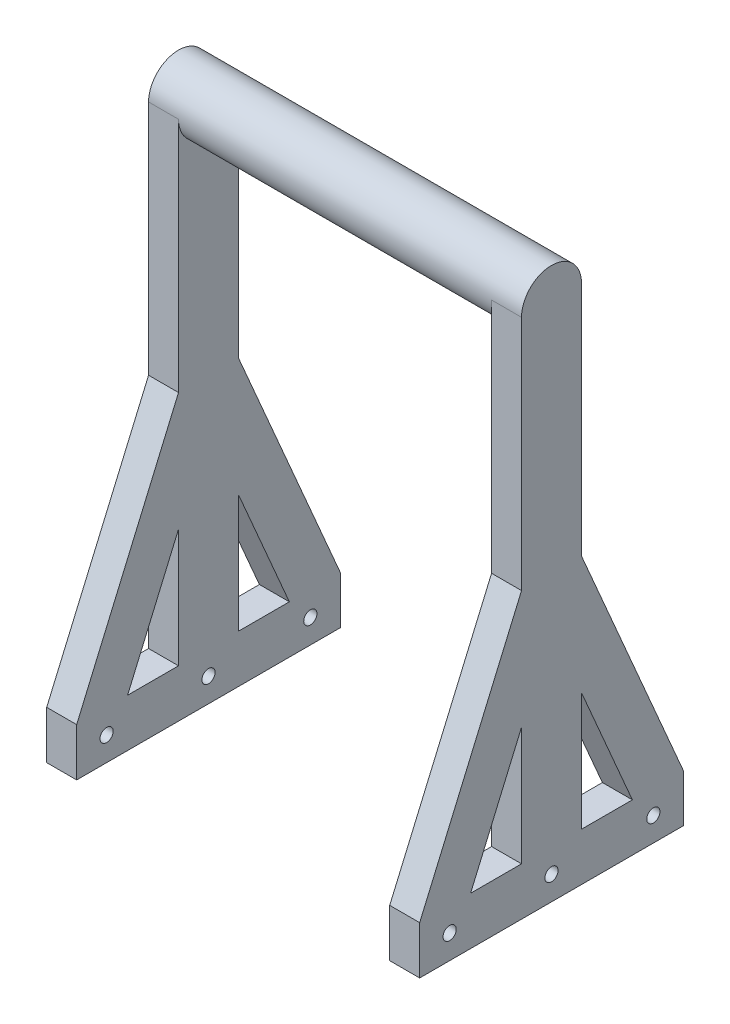
SolidWorks part; units mm, degrees
ref_plane "前视基准面" through (0, 0, 0) normal (0, 0, 1) x (1, 0, 0)
ref_plane "上视基准面" through (0, 0, 0) normal (0, 1, 0) x (1, 0, 0)
ref_plane "右视基准面" through (0, 0, 0) normal (1, 0, 0) x (0, 0, -1)
sketch "草图2" plane through (0, 0, 0) normal (0, 1, 0) x (1, 0, 0)
  line L0 (0, 27.4644) -> (0, -23.7489) construction
  line L1 (-36.2271, 0) -> (41.5528, 0) construction
  line L3 (-62.25, 44) -> (-52.25, 44)
  line L4 (-62.25, 44) -> (-62.25, -44)
  line L5 (-62.25, -44) -> (-52.25, -44)
  line L6 (-52.25, 44) -> (-52.25, -44)
  line L7 (-62.25, 44) -> (-52.25, -44) construction
  line L8 (-62.25, -44) -> (-52.25, 44) construction
  line L9 (52.25, 44) -> (62.25, 44)
  line L10 (52.25, 44) -> (52.25, -44)
  line L11 (52.25, -44) -> (62.25, -44)
  line L12 (62.25, 44) -> (62.25, -44)
  line L13 (52.25, 44) -> (62.25, -44) construction
  line L14 (52.25, -44) -> (62.25, 44) construction
  point P5 (-57.25, 0)
  point P10 (57.25, 0)
  dimension "D1" = 52.25
  dimension "D2" = 52.25
  dimension "D3" = 10
  dimension "D4" = 10
  dimension "D5" = 88
  dimension "D6" = 88
extrude "凸台-拉伸1" add sketch "草图2" along normal blind 16
sketch "草图3" plane through (0, 16, 0) normal (0, 1, 0) x (1, 0, 0)
  line L0 (0, 44.2315) -> (0, -45.1645) construction
  line L1 (-40.542, 0) -> (49.5325, 0) construction
  line L2 (-62.25, 44) -> (-62.25, -44) construction
  line L3 (-62.25, 10) -> (-52.25, 10)
  line L4 (-62.25, 10) -> (-62.25, -10)
  line L5 (-62.25, -10) -> (-52.25, -10)
  line L6 (-52.25, 10) -> (-52.25, -10)
  line L7 (-52.25, -44) -> (-52.25, 44) construction
  line L8 (62.25, -10) -> (52.25, -10)
  line L9 (52.25, 10) -> (52.25, -10)
  line L10 (62.25, 10) -> (52.25, 10)
  line L11 (62.25, 10) -> (62.25, -10)
  dimension "D1" = 10
  dimension "D2" = 10
extrude "凸台-拉伸2" add sketch "草图3" along normal blind 158
sketch "草图4" plane through (-62.25, 0, 0) normal (-1, 0, 0) x (0, 0, 1)
  line L0 (-10, 174) -> (10, 174) construction
  circle A0 centre (0, 174) radius 10
extrude "凸台-拉伸3" add sketch "草图4" against normal blind 124.5
sketch "草图5" plane through (-62.25, 0, 0) normal (-1, 0, 0) x (0, 0, 1)
  line L0 (-44, 8) -> (44, 8) construction
  line L1 (-44, 16) -> (-44, 0) construction
  line L2 (44, 16) -> (44, 0) construction
  line L3 (0, 112.2704) -> (0, 0) construction
  circle A0 centre (0, 8) radius 2.2
  circle A1 centre (-34, 8) radius 2.2
  circle A2 centre (34, 8) radius 2.2
  dimension "D1" = 4.4
  dimension "D2" = 4.4
  dimension "D3" = 4.4
  dimension "D4" = 34
  dimension "D5" = 34
extrude "切除-拉伸1" cut sketch "草图5" against normal blind 126
sketch "草图6" plane through (-62.25, 0, 0) normal (-1, 0, 0) x (0, 0, 1)
  line L0 (-44, 16) -> (-10, 95)
  line L1 (-10, 174) -> (-10, 16) construction
  line L2 (-27, 16) -> (-10, 55.5)
  line L3 (-44, 16) -> (-10, 16) construction
  line L4 (-44, 16) -> (-27, 16)
  line L5 (-10, 95) -> (-10, 55.5)
  line L6 (0, 0) -> (0, 51.1934) construction
  line L7 (-44, 0) -> (44, 0) construction
  line L8 (44, 16) -> (10, 95)
  line L9 (44, 16) -> (27, 16)
  line L10 (27, 16) -> (10, 55.5)
  line L11 (10, 95) -> (10, 55.5)
extrude "凸台-拉伸4" add sketch "草图6" against normal blind 10
sketch "草图7" plane through (62.25, 0, 0) normal (1, 0, 0) x (0, 0, -1)
  line L0 (0, 0) -> (0, 117.2713) construction
  line L1 (-44, 0) -> (44, 0) construction
  line L2 (-44, 16) -> (-10, 95)
  line L3 (-10, 174) -> (-10, 16) construction
  line L4 (-27, 16) -> (-10, 55.5)
  line L5 (-44, 16) -> (-10, 16) construction
  line L6 (-10, 55.5) -> (-10, 16) construction
  line L7 (-10, 95) -> (-10, 55.5)
  line L8 (-44, 16) -> (-27, 16)
  line L9 (44, 16) -> (10, 95)
  line L10 (10, 95) -> (10, 55.5)
  line L11 (27, 16) -> (10, 55.5)
  line L12 (44, 16) -> (27, 16)
extrude "凸台-拉伸5" add sketch "草图7" against normal blind 10
